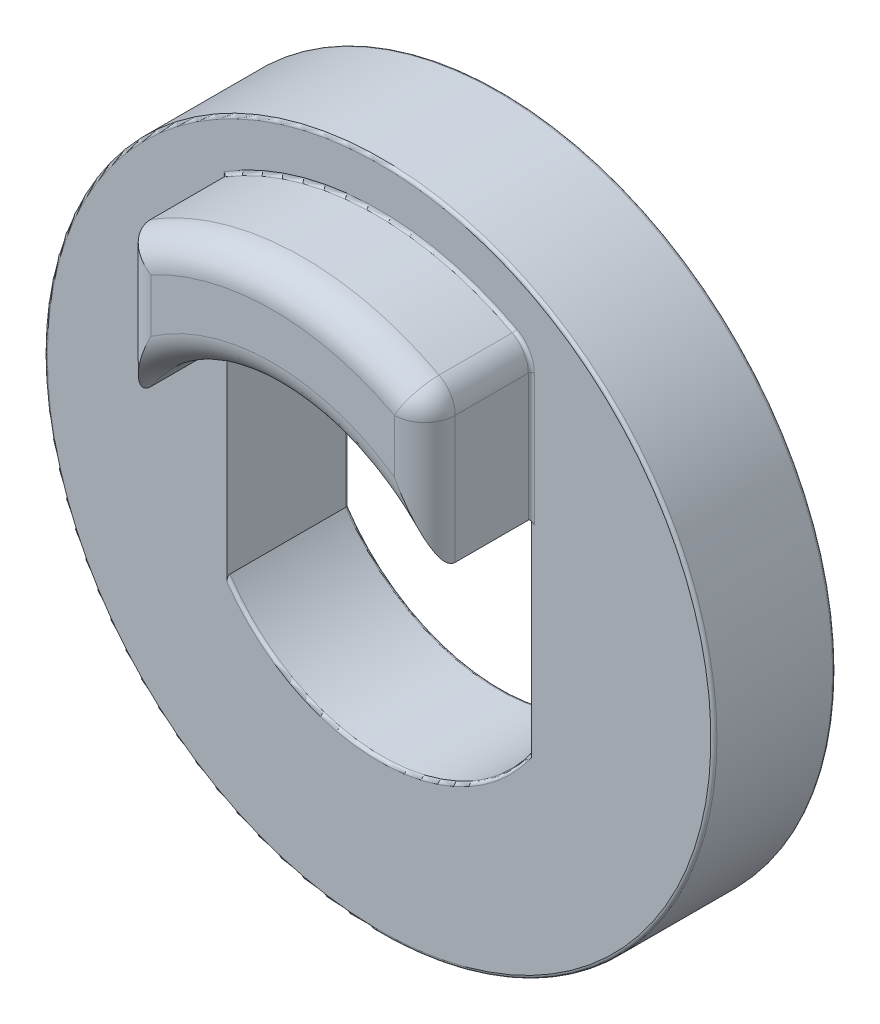
SolidWorks part; units mm, degrees
ref_plane "Alzado" through (0, 0, 0) normal (0, 0, 1) x (1, 0, 0)
ref_plane "Planta" through (0, 0, 0) normal (0, 1, 0) x (1, 0, 0)
ref_plane "Vista lateral" through (0, 0, 0) normal (1, 0, 0) x (0, 0, -1)
sketch "Croquis2" plane through (0, 0, 0) normal (1, 0, 0) x (0, 0, -1)
  line L0 (-7.5, 6) -> (0, 6)
  line L1 (-7.5, 0) -> (7.5, 0) construction
  line L2 (-7.5, 6) -> (-7.5, 9.5)
  line L3 (-7.5, 9.5) -> (-4, 9.5)
  line L4 (-4, 9.5) -> (-4, 11)
  line L5 (-4, 11) -> (0, 11)
  line L6 (0, 11) -> (0, 6)
  point P3 (-3.75, 6)
  point P7 (0, 0)
  dimension "D1" = 12
  dimension "D2" = 7.5
  dimension "D3" = 3.5
  dimension "D4" = 3.5
  dimension "D5" = 1.5
revolve "Revolución1" add sketch "Croquis2" angle 360 about L1
sketch "Croquis3" plane through (0, 0, 7.5) normal (0, 0, 1) x (1, 0, 0)
  line L1 (-5, 8.0777) -> (5, 8.0777)
  line L2 (-5, 8.0777) -> (-5, -8.0777)
  line L3 (-5, -8.0777) -> (5, -8.0777)
  line L4 (5, 8.0777) -> (5, -8.0777)
  line L5 (-5, 8.0777) -> (5, -8.0777) construction
  line L6 (-5, -8.0777) -> (5, 8.0777) construction
  circle A0 centre (0, 0) radius 9.5 construction
  circle A1 centre (0, 0) radius 6 construction
  circle A2 centre (0, 0) radius 9.5
  circle A3 centre (0, 0) radius 6
  circle M5 centre (0, 0) radius 6
  dimension "D1" = 10
extrude "Saliente-Extruir1" add sketch "Croquis3" against normal through all contours L4 M5 | L2 M5
sketch "Croquis4" plane through (0, 0, 7.5) normal (0, 0, 1) x (1, 0, 0)
  line L0 (5, 3.3166) -> (5, -3.3166) construction
  line L1 (-5, 8.0777) -> (5, 8.0777)
  line L2 (-5, 8.0777) -> (-5, -8.0777)
  line L3 (-5, -8.0777) -> (5, -8.0777)
  line L4 (5, 8.0777) -> (5, -8.0777)
  line L5 (-5, 8.0777) -> (5, -8.0777) construction
  line L6 (-5, -8.0777) -> (5, 8.0777) construction
  circle A0 centre (0, 0) radius 9.5 construction
  circle A1 centre (0, 0) radius 9.5
  point P9 (5, 0)
  point P10 (5, 0)
  line M3 (5, 3.3166) -> (5, -3.3166)
  arc M4 (5, -3.3166) -> (-5, -3.3166) centre (0, 0) cw
  line M5 (-5, -3.3166) -> (-5, 3.3166)
  circle M6 centre (0, 0) radius 9.5
extrude "Cortar-Extruir1" cut sketch "Croquis4" against normal up to surface (3.5 mm away) contours L4 M6 M3 | L2 M6 M5 | L4 L2 L3 M4 | L3 M6 up to face at (9.5, 0, 4)
fillet "Redondeo1" radius 1 5 edges at (-5, 5.6972, 7.5) (0, 6, 7.5) (5, 5.6972, 7.5) (5, 8.0777, 5.75) (0, 9.5, 7.5)
fillet "Redondeo2" radius 0.1 8 edges at (5, 0, 0) (0, -6, 0) (-5, 0, 0) (0, 6, 0) (-0.3054, 9.4951, 4) (4.8575, 8.0145, 4) (11, 0, 4) (11, 0, 0)
